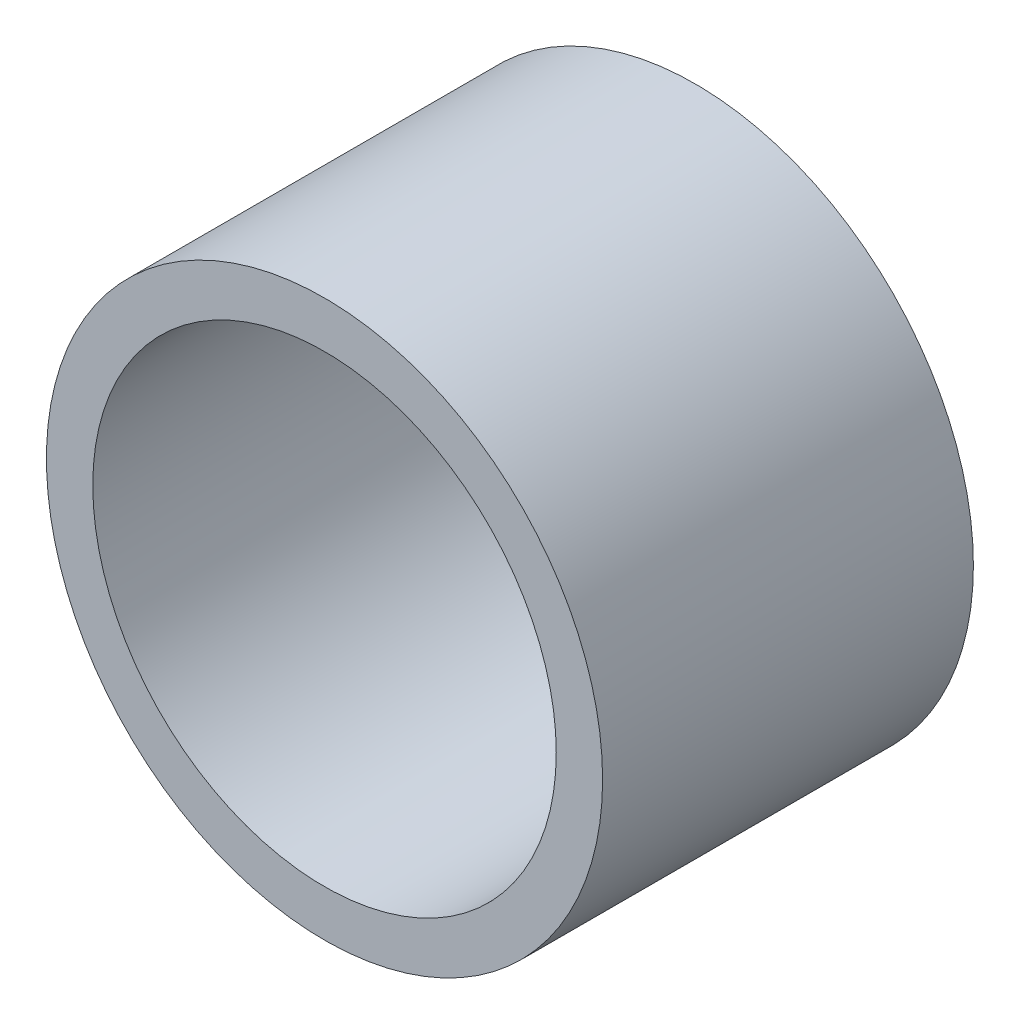
SolidWorks part; units mm, degrees
ref_plane "Plan de face" through (0, 0, 0) normal (0, 0, 1) x (1, 0, 0)
ref_plane "Plan de dessus" through (0, 0, 0) normal (0, 1, 0) x (1, 0, 0)
ref_plane "Plan de droite" through (0, 0, 0) normal (1, 0, 0) x (0, 0, -1)
sketch "Esquisse1" plane through (0, 0, 0) normal (0, 0, 1) x (1, 0, 0)
  circle A0 centre (0, 0) radius 5
  circle A1 centre (0, 0) radius 6
extrude "Boss.-Extru.1" add sketch "Esquisse1" along normal blind 8
